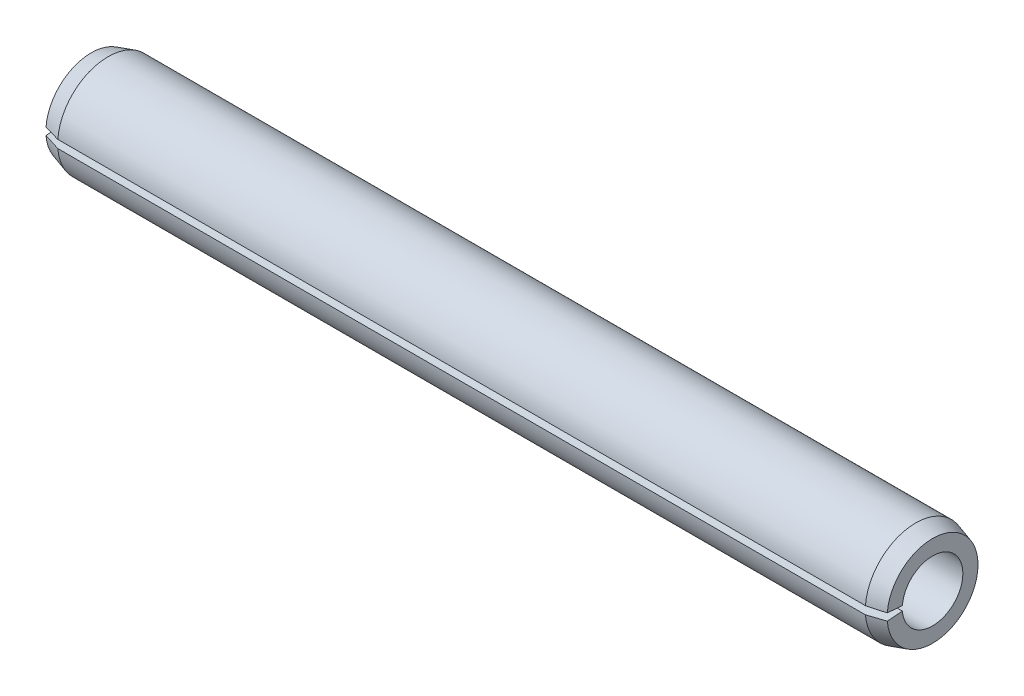
SolidWorks part; units mm, degrees
ref_plane "Plane1" through (0, 0, 0) normal (0, 0, 1) x (1, 0, 0)
ref_plane "Plane2" through (0, 0, 0) normal (0, 1, 0) x (1, 0, 0)
ref_plane "Plane3" through (0, 0, 0) normal (1, 0, 0) x (0, 0, -1)
sketch "Sketch1" plane through (0, 0, 0) normal (0, 0, 1) x (1, 0, 0)
  line L0 (-9.525, 0) -> (111.125, 0) construction
  line L1 (0, 0.9) -> (25, 0.9)
  line L2 (25, 0.9) -> (25, 1.35)
  line L3 (25, 1.35) -> (24.5, 1.5)
  line L4 (24.5, 1.5) -> (0.5, 1.5)
  line L5 (0.5, 1.5) -> (0, 1.35)
  line L7 (0, 1.35) -> (0, 0.9)
  dimension "Diameter" = 3
  dimension "Thickness" = 0.6
  dimension "Length" = 25
  dimension "Chamfer_len" = 0.5
  dimension "D1" = 2.7
  dimension "D2" = 2.7
  dimension "D3" = 0.5
revolve "Base-Revolve" add sketch "Sketch1" angle 360 about L0
sketch "Sketch2" plane through (0, 0, 0) normal (-1, 0, 0) x (0, -1, 0)
  line L0 (0, 0) -> (0.12, 1.5253)
  line L1 (0, -3.175) -> (0, 12.7) construction
  line L2 (0, 0) -> (-0.12, 1.5253)
  arc A0 (0.12, 1.5253) -> (-0.12, 1.5253) centre (0, 0) ccw
  dimension "Gap_ang" = 9
  dimension "D1" = 1.53
extrude "Gap" cut sketch "Sketch2" against normal through all
equation "\"D1@Sketch2\" = \"Diameter@Sketch1\" * 0.51"
equation "\"D1@Sketch1\" = \"Diameter@Sketch1\" -  ( \"Thickness@Sketch1\" / 2 ) "
equation "\"D2@Sketch1\" = \"D1@Sketch1\""
equation "\"D3@Sketch1\" = \"Chamfer_len@Sketch1\""
